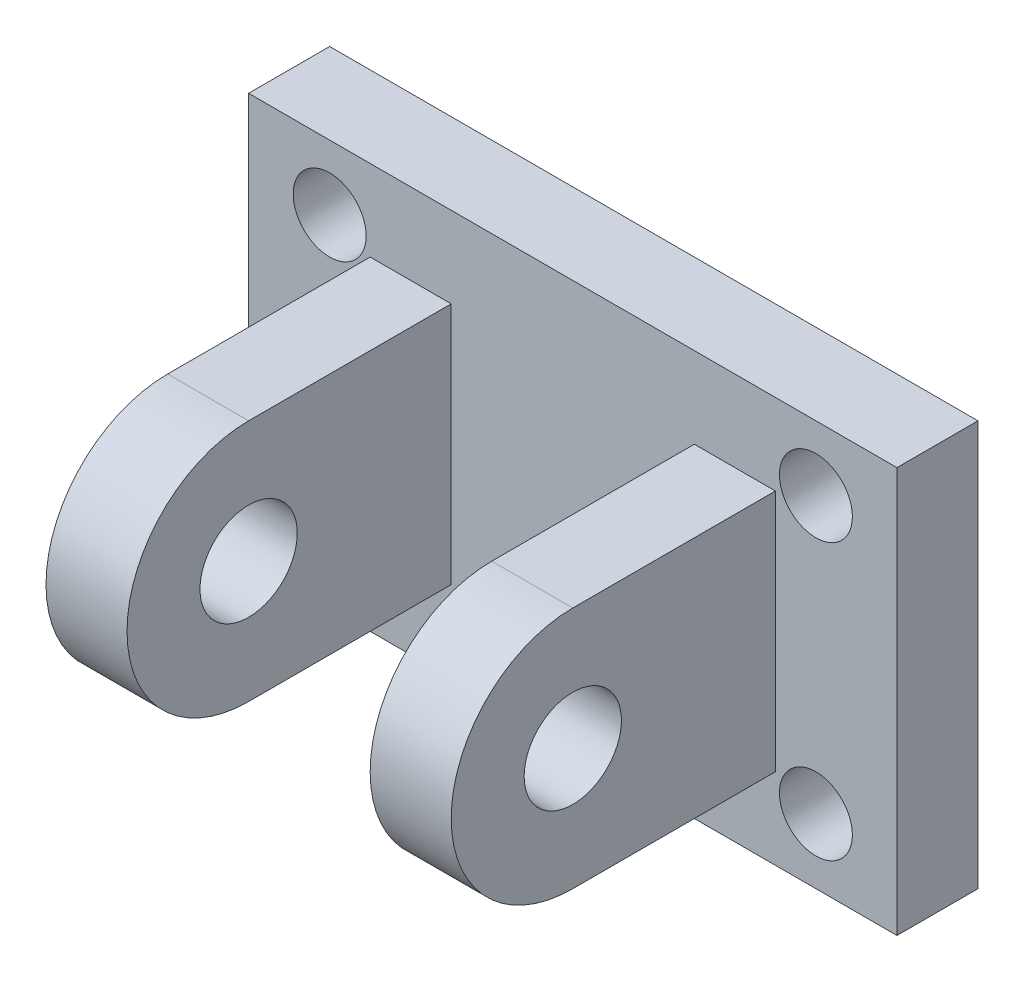
SolidWorks part; units mm, degrees
ref_plane "前视基准面" through (0, 0, 0) normal (0, 0, 1) x (1, 0, 0)
ref_plane "上视基准面" through (0, 0, 0) normal (0, 1, 0) x (1, 0, 0)
ref_plane "右视基准面" through (0, 0, 0) normal (1, 0, 0) x (0, 0, -1)
sketch "草图1" plane through (0, 0, 0) normal (0, 0, 1) x (1, 0, 0)
  line L0 (-40, -25) -> (40, -25)
  line L1 (40, -25) -> (40, 25)
  line L2 (40, 25) -> (-40, 25)
  line L3 (-40, 25) -> (-40, -25)
extrude "凸台-拉伸1" add sketch "草图1" along normal blind 10
ref_plane "基准面1" through (15, 0, 0) normal (1, 0, 0) x (0, 0, -1)
sketch "草图2" plane through (15, 0, 0) normal (1, 0, 0) x (0, 0, -1)
  line L0 (-9.5, -15) -> (-35, -15)
  line L1 (-35, 15) -> (-9.5, 15)
  line L2 (-9.5, 15) -> (-9.5, -15)
  arc A0 (-35, -15) -> (-35, 15) centre (-35, 0) cw
extrude "凸台-拉伸2" add sketch "草图2" along normal blind 10
mirror "镜向1" about plane through (0, 0, 0) normal (1, 0, 0) of "凸台-拉伸2"
ref_plane "基准面2" through (-25, 0, 0) normal (1, 0, 0) x (0, 0, -1)
sketch "草图3" plane through (-25, 0, 0) normal (1, 0, 0) x (0, 0, -1)
  circle A0 centre (-35, 0) radius 6
extrude "切除-拉伸1" cut sketch "草图3" along normal through all
sketch "草图4" plane through (0, 0, 0) normal (0, 0, 1) x (1, 0, 0)
  circle A0 centre (30, 17) radius 4.5
  circle A1 centre (30, -17) radius 4.5
  circle A2 centre (-30, 17) radius 4.5
  circle A3 centre (-30, -17) radius 4.5
extrude "切除-拉伸2" cut sketch "草图4" along normal through all
